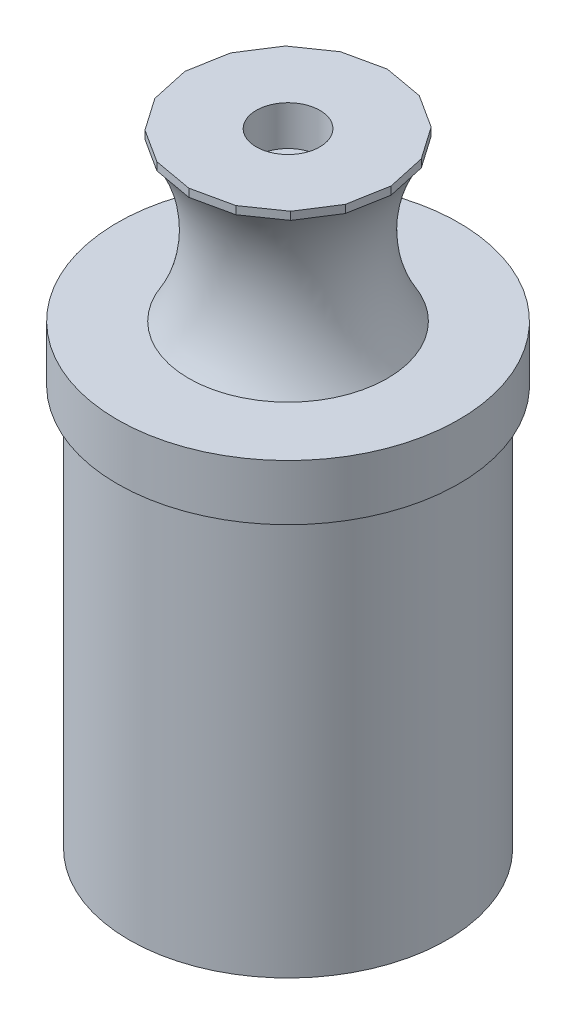
SolidWorks part; units mm, degrees
material "1060 Alloy"
ref_plane "Front Plane" through (0, 0, 0) normal (0, 0, 1) x (1, 0, 0)
ref_plane "Top Plane" through (0, 0, 0) normal (0, 1, 0) x (1, 0, 0)
ref_plane "Right Plane" through (0, 0, 0) normal (1, 0, 0) x (0, 0, -1)
sketch "Sketch1" plane through (0, 0, 0) normal (0, 1, 0) x (1, 0, 0)
  circle A0 centre (0, 0) radius 20
  dimension "D1" = 40
extrude "Boss-Extrude1" add sketch "Sketch1" along normal blind 50.5
sketch "Sketch2" plane through (0, 50.5, 0) normal (0, 1, 0) x (1, 0, 0)
  circle A0 centre (0, 0) radius 21.5
  dimension "D1" = 43
extrude "Boss-Extrude2" add sketch "Sketch2" along normal blind 7
sketch "Sketch3" plane through (0, 0, 0) normal (0, 0, 1) x (1, 0, 0)
  line L0 (0, 57.5) -> (0, 77.5) construction
  line L1 (21.5, 57.5) -> (-21.5, 57.5) construction
  line L2 (0, -55) -> (0, 55) construction
  line L3 (0, 77.5) -> (12.5, 77.5)
  line L4 (0, 77.5) -> (0, 57.5)
  line L5 (0, 57.5) -> (12.5, 57.5)
  arc A0 (12.5, 77.5) -> (12.5, 57.5) centre (28.7846, 67.5) ccw
  dimension "D1" = 20
  dimension "D2" = 12.5
  dimension "D3" = 12.5
revolve "Revolve1" add sketch "Sketch3" angle 360 about L0
sketch "Sketch4" plane through (0, 77.5, 0) normal (0, 1, 0) x (1, 0, 0)
  line L21 (8.8418, 9.179) -> (4.6561, 11.8639)
  line L22 (4.6561, 11.8639) -> (-0.2384, 12.7427)
  line L23 (-0.2384, 12.7427) -> (-5.0967, 11.6814)
  line L24 (-5.0967, 11.6814) -> (-9.179, 8.8418)
  line L25 (-9.179, 8.8418) -> (-11.8639, 4.6561)
  line L26 (-11.8639, 4.6561) -> (-12.7427, -0.2384)
  line L27 (-12.7427, -0.2384) -> (-11.6814, -5.0967)
  line L28 (-11.6814, -5.0967) -> (-8.8418, -9.179)
  line L29 (-8.8418, -9.179) -> (-4.6561, -11.8639)
  line L30 (-4.6561, -11.8639) -> (0.2384, -12.7427)
  line L31 (0.2384, -12.7427) -> (5.0967, -11.6814)
  line L32 (5.0967, -11.6814) -> (9.179, -8.8418)
  line L33 (9.179, -8.8418) -> (11.8639, -4.6561)
  line L34 (11.8639, -4.6561) -> (12.7427, 0.2384)
  line L35 (12.7427, 0.2384) -> (11.6814, 5.0967)
  line L36 (11.6814, 5.0967) -> (8.8418, 9.179)
  circle A0 centre (0, 0) radius 12.5 construction
extrude "Boss-Extrude3" add sketch "Sketch4" along normal blind 1
sketch "Sketch5" plane through (0, 0, 0) normal (0, -1, 0) x (1, 0, 0)
  circle A0 centre (0, 0) radius 5
extrude "Cut-Extrude1" cut sketch "Sketch5" against normal blind 1
sketch "Sketch6" plane through (0, 78.5, 0) normal (0, 1, 0) x (1, 0, 0)
  circle A0 centre (0, 0) radius 4
extrude "Cut-Extrude2" cut sketch "Sketch6" against normal blind 5
